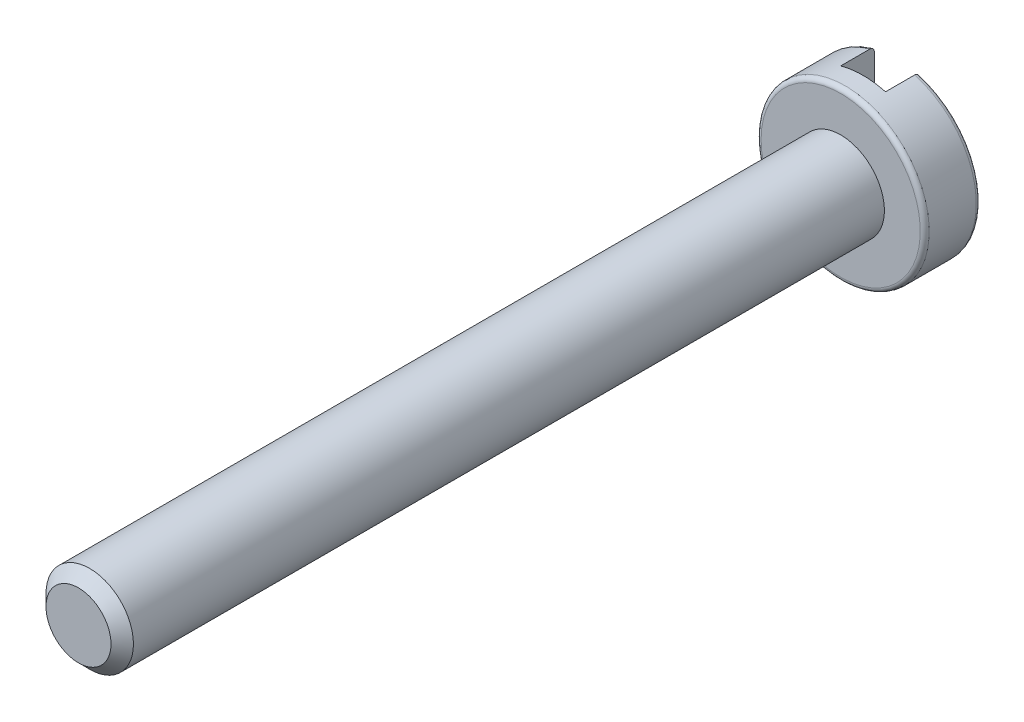
SolidWorks part; units mm, degrees
ref_plane "Front Plane" through (0, 0, 0) normal (0, 0, 1) x (1, 0, 0)
ref_plane "Top Plane" through (0, 0, 0) normal (0, 1, 0) x (1, 0, 0)
ref_plane "Right Plane" through (0, 0, 0) normal (1, 0, 0) x (0, 0, -1)
sketch "Sketch2" plane through (0, 0, 0) normal (0, 0, 1) x (1, 0, 0)
  circle A0 centre (0, 0) radius 1.95
  dimension "D1" = 3.9
extrude "Boss-Extrude1" add sketch "Sketch2" along normal blind 34
sketch "Sketch3" plane through (0, 0, 0) normal (0, 0, -1) x (-1, 0, 0)
  circle A0 centre (0, 0) radius 3.75
  dimension "D1" = 7.5
extrude "Boss-Extrude2" add sketch "Sketch3" along normal blind 2.5
sketch "Sketch4" plane through (0, 0, -2.5) normal (0, 0, -1) x (-1, 0, 0)
  line L1 (1, -5) -> (-1, -5)
  line L2 (1, -5) -> (1, 5)
  line L3 (1, 5) -> (-1, 5)
  line L4 (-1, -5) -> (-1, 5)
  line L5 (1, -5) -> (-1, 5) construction
  line L6 (1, 5) -> (-1, -5) construction
  point P0 (0, 0)
  point P6 (0, 5)
  dimension "D1" = 2
  dimension "D2" = 5
extrude "Cut-Extrude1" cut sketch "Sketch4" against normal blind 1.5
fillet "Fillet1" radius 0.2 3 edges at (-3.75, 0, 0) (-3.75, 0, -2.5) (3.75, 0, -2.5)
chamfer "Chamfer1" distance 0.5 angle 45 1 edges at (1.95, 0, 34)
